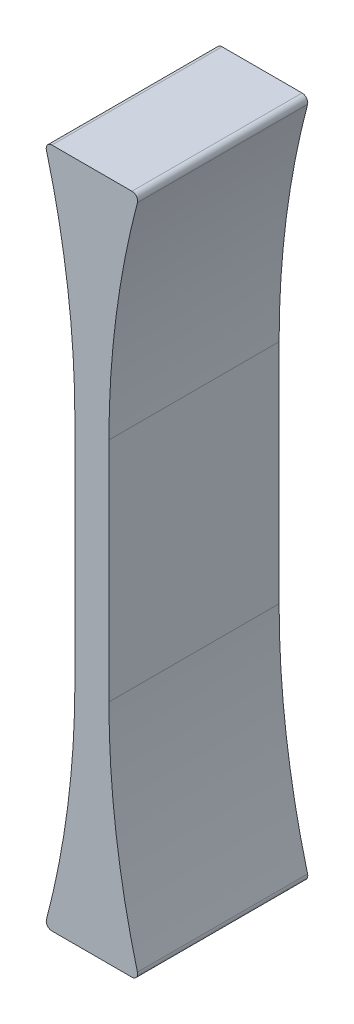
SolidWorks part; units mm, degrees
ref_plane "Front Plane" through (0, 0, 0) normal (0, 0, 1) x (1, 0, 0)
ref_plane "Top Plane" through (0, 0, 0) normal (0, 1, 0) x (1, 0, 0)
ref_plane "Right Plane" through (0, 0, 0) normal (1, 0, 0) x (0, 0, -1)
sketch "Sketch1" plane through (0, 0, 0) normal (0, 0, 1) x (1, 0, 0)
  line L0 (0, 0) -> (1.5, 0)
  line L5 (1.5, 0) -> (1.5, 10)
  line L7 (4.1788, 30) -> (0, 30)
  line L8 (0, 30) -> (0, 0)
  arc A0 (1.5, 10) -> (4.1788, 30) centre (77.5, 10) cw
  point P7 (1.5, 9.3845)
  point P8 (4.4266, 19.7605)
  point P9 (1.5, 6.554)
  dimension "D2" = 76
  dimension "D1" = 30
  dimension "1.5" = 1.5
  dimension "D3" = 10
extrude "Boss-Extrude1" add sketch "Sketch1" along normal blind 15
mirror "Mirror1" about plane through (0, 30, 15) normal (1, 0, 0) of "Boss-Extrude1"
mirror "Mirror6" about plane through (0, 0, 15) normal (0, 1, 0) of bodies 102
fillet "Fillet1" radius 0.5 4 edges at (-4.1788, -30, 7.5) (4.1788, -30, 7.5) (-4.1788, 30, 7.5) (4.1788, 30, 7.5)
